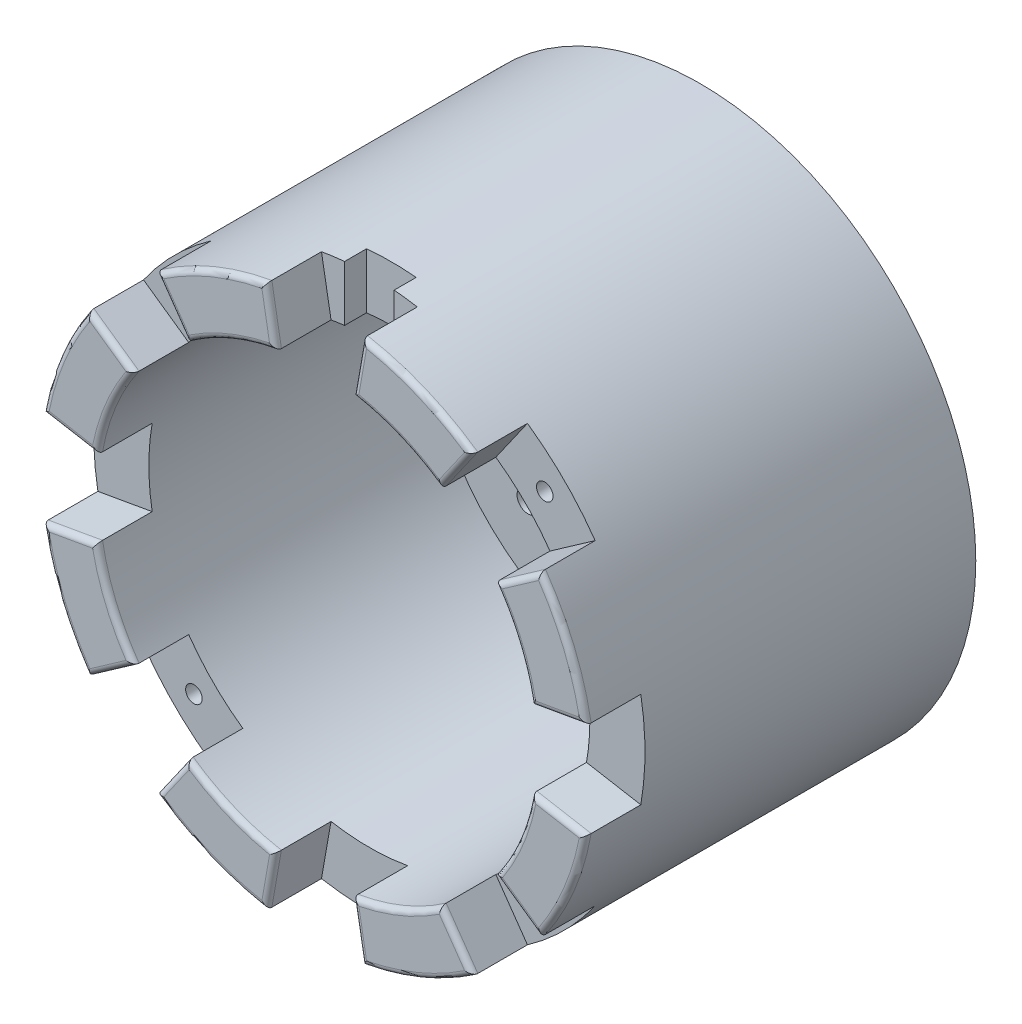
SolidWorks part; units mm, degrees
ref_plane "Alzado" through (0, 0, 0) normal (0, 0, 1) x (1, 0, 0)
ref_plane "Planta" through (0, 0, 0) normal (0, 1, 0) x (1, 0, 0)
ref_plane "Vista lateral" through (0, 0, 0) normal (1, 0, 0) x (0, 0, -1)
sketch "Croquis1" plane through (0, 0, 0) normal (0, 0, 1) x (1, 0, 0)
  circle A0 centre (0, 0) radius 50
  circle A1 centre (0, 0) radius 17.75
  dimension "D1" = 100
  dimension "D2" = 35.5
extrude "Saliente-Extruir1" add sketch "Croquis1" along normal blind 70
sketch "Croquis2" plane through (0, 0, 70) normal (0, 0, 1) x (1, 0, 0)
  circle A0 centre (0, 0) radius 40
  dimension "D1" = 80
extrude "Cortar-Extruir1" cut sketch "Croquis2" against normal blind 50
sketch "Croquis4" plane through (0, 0, 20) normal (0, 0, 1) x (1, 0, 0)
  line L1 (-2.5, 32.5) -> (2.5, 32.5)
  line L2 (-2.5, 32.5) -> (-2.5, 22.5)
  line L3 (-2.5, 22.5) -> (2.5, 22.5)
  line L4 (2.5, 32.5) -> (2.5, 22.5)
  line L5 (-2.5, 32.5) -> (2.5, 22.5) construction
  line L6 (-2.5, 22.5) -> (2.5, 32.5) construction
  line L7 (32.5, -2.5) -> (22.5, -2.5)
  line L8 (32.5, -2.5) -> (32.5, 2.5)
  line L9 (32.5, 2.5) -> (22.5, 2.5)
  line L10 (22.5, -2.5) -> (22.5, 2.5)
  line L11 (32.5, -2.5) -> (22.5, 2.5) construction
  line L12 (32.5, 2.5) -> (22.5, -2.5) construction
  line L13 (2.5, -32.5) -> (-2.5, -32.5)
  line L14 (2.5, -32.5) -> (2.5, -22.5)
  line L15 (2.5, -22.5) -> (-2.5, -22.5)
  line L16 (-2.5, -32.5) -> (-2.5, -22.5)
  line L17 (2.5, -32.5) -> (-2.5, -22.5) construction
  line L18 (2.5, -22.5) -> (-2.5, -32.5) construction
  line L19 (-32.5, -2.5) -> (-22.5, -2.5)
  line L20 (-32.5, -2.5) -> (-32.5, 2.5)
  line L21 (-32.5, 2.5) -> (-22.5, 2.5)
  line L22 (-22.5, -2.5) -> (-22.5, 2.5)
  line L23 (-32.5, -2.5) -> (-22.5, 2.5) construction
  line L24 (-32.5, 2.5) -> (-22.5, -2.5) construction
  circle A0 centre (0, 0) radius 40
  circle A1 centre (0, 0) radius 27.5
  point P4 (0, 27.5)
  point P9 (27.5, 0)
  point P14 (0, -27.5)
  point P19 (-27.5, 0)
  circle M10 centre (0, 0) radius 17.75
  circle M11 centre (0, 0) radius 40
  dimension "D1" = 80
  dimension "D2" = 55
  dimension "D3" = 10
  dimension "D4" = 5
  dimension "D5" = 5
  dimension "D6" = 10
  dimension "D7" = 5
  dimension "D8" = 10
  dimension "D9" = 5
  dimension "D10" = 10
extrude "Cortar-Extruir3" cut sketch "Croquis4" against normal blind 10 contours A1 L9 L8 L7 L14 L13 L16 L19 L20 L21 L2 L1 L4 M11 | L9 A1 L4 L3 L2 L21 L22 L19 L16 L15 L14 L7 L10 M10
sketch "Croquis5" plane through (0, 0, 10) normal (0, 0, 1) x (1, 0, 0)
  line L0 (0, 0) -> (28.2843, 28.2843) construction
  circle A0 centre (21.2132, 21.2132) radius 2
  circle A1 centre (21.2132, -21.2132) radius 2
  circle A2 centre (-21.2132, -21.2132) radius 2
  circle A3 centre (-21.2132, 21.2132) radius 2
  point P14 (0, 0)
  dimension "D2" = 4
  dimension "D1" = 40
  dimension "D4" = 30
  dimension "D3" = 4
extrude "Cortar-Extruir4" cut sketch "Croquis5" against normal through all
sketch "Croquis6" plane through (0, 0, 0) normal (0, 0, -1) x (-1, 0, 0)
  circle A0 centre (-21.2132, 21.2132) radius 5
  circle A1 centre (21.487, 21.487) radius 5
  circle A2 centre (21.7607, -21.2132) radius 5
  circle A3 centre (-20.9394, -21.487) radius 5
  point P12 (0.2738, 0)
  dimension "D1" = 10
  dimension "D2" = 4
extrude "Cortar-Extruir5" cut sketch "Croquis6" against normal blind 5
sketch "Croquis7" plane through (0, 0, 70) normal (0, 0, 1) x (1, 0, 0)
  line L0 (0, 0) -> (0, 50)
  line L1 (0, 0) -> (8.6824, 49.2404)
  line L2 (0, 0) -> (-8.6824, 49.2404)
  line L3 (0, 0) -> (40.9576, 28.6788)
  line L4 (0, 0) -> (28.6788, 40.9576)
  line L5 (0, 0) -> (49.2404, -8.6824)
  line L6 (0, 0) -> (49.2404, 8.6824)
  line L7 (0, 0) -> (28.6788, -40.9576)
  line L8 (0, 0) -> (40.9576, -28.6788)
  line L9 (0, 0) -> (-8.6824, -49.2404)
  line L10 (0, 0) -> (8.6824, -49.2404)
  line L11 (0, 0) -> (-40.9576, -28.6788)
  line L12 (0, 0) -> (-28.6788, -40.9576)
  line L13 (0, 0) -> (-49.2404, 8.6824)
  line L14 (0, 0) -> (-49.2404, -8.6824)
  line L15 (0, 0) -> (-28.6788, 40.9576)
  line L16 (0, 0) -> (-40.9576, 28.6788)
  circle A0 centre (0, 0) radius 50 construction
  circle A1 centre (0, 0) radius 40
  circle A2 centre (0, 0) radius 50
  point P27 (0, 0)
  circle M5 centre (0, 0) radius 40
  circle M6 centre (0, 0) radius 50
  dimension "D3" = 100
  dimension "D4" = 80
  dimension "D1" = 10
  dimension "D2" = 10
  dimension "D5" = 8
extrude "Cortar-Extruir6" cut sketch "Croquis7" against normal blind 10 contours L2 L0 M5 M6 | L1 L0 M5 M6 | L4 L3 M5 M6 | L6 L5 M5 M6 | L8 L7 M5 M6 | L16 L15 M5 M6 | L14 L13 M5 M6 | L12 L11 M5 M6 | L10 L9 M5 M6
fillet "Redondeo2" radius 1 48 edges at (7.8142, 44.3163, 70) (19.1342, 46.194, 70) (25.8109, 36.8618, 70) (15.3073, 36.9552, 70) (36.8618, 25.8109, 70) (46.194, 19.1342, 70) (44.3163, 7.8142, 70) (36.9552, 15.3073, 70) (44.3163, -7.8142, 70) (46.194, -19.1342, 70) (36.8618, -25.8109, 70) (36.9552, -15.3073, 70) (19.1342, -46.194, 70) (7.8142, -44.3163, 70) (15.3073, -36.9552, 70) (25.8109, -36.8618, 70) (-7.8142, -44.3163, 70) (-19.1342, -46.194, 70) (-25.8109, -36.8618, 70) (-15.3073, -36.9552, 70) (-19.1342, 46.194, 70) (-7.8142, 44.3163, 70) (-15.3073, 36.9552, 70) (-25.8109, 36.8618, 70) (-36.8618, -25.8109, 70) (-46.194, -19.1342, 70) (-44.3163, -7.8142, 70) (-36.9552, -15.3073, 70) (-44.3163, 7.8142, 70) (-46.194, 19.1342, 70) (-36.8618, 25.8109, 70) (-36.9552, 15.3073, 70) (0, -22.5, 20) (2.5, -27.5, 20) (0, -32.5, 20) (-2.5, -27.5, 20) (-32.5, 0, 20) (-27.5, 2.5, 20) (-22.5, 0, 20) (-27.5, -2.5, 20) (22.5, 0, 20) (27.5, 2.5, 20) (32.5, 0, 20) (27.5, -2.5, 20) (0, 22.5, 20) (-2.5, 27.5, 20) (0, 32.5, 20) (2.5, 27.5, 20)
sketch "Croquis8" plane through (0, 0, 70) normal (0, 0, 1) x (1, 0, 0)
  line L0 (0, 0) -> (0, 52.9149) construction
  line L2 (-4.5, 55) -> (4.5, 55)
  line L3 (-4.5, 55) -> (-4.5, 35)
  line L4 (-4.5, 35) -> (4.5, 35)
  line L5 (4.5, 55) -> (4.5, 35)
  line L6 (-4.5, 55) -> (4.5, 35) construction
  line L7 (-4.5, 35) -> (4.5, 55) construction
  point P3 (0, 45)
  dimension "D1" = 9
  dimension "D2" = 20
  dimension "D3" = 45
extrude "Cortar-Extruir7" cut sketch "Croquis8" against normal blind 4 from offset 10 offset against normal yes
sketch "Croquis9" plane through (0, 0, 60) normal (0, 0, 1) x (1, 0, 0)
  line L0 (0, 0) -> (42.0938, 42.0938) construction
  line L1 (0, 0) -> (50, 0) construction
  circle A0 centre (31.8198, 31.8198) radius 1.5
  circle A2 centre (0, 0) radius 40 construction
  arc A3 (49.2404, -8.6824) -> (49.2404, 8.6824) centre (0, 0) ccw construction
  circle A4 centre (31.8198, -31.8198) radius 1.5
  circle A5 centre (-31.8198, -31.8198) radius 1.5
  circle A6 centre (-31.8198, 31.8198) radius 1.5
  point P20 (0, 0)
  dimension "D2" = 3
  dimension "D1" = 45
  dimension "D3" = 45
  dimension "D4" = 4
extrude "Cortar-Extruir8" cut sketch "Croquis9" against normal blind 20
